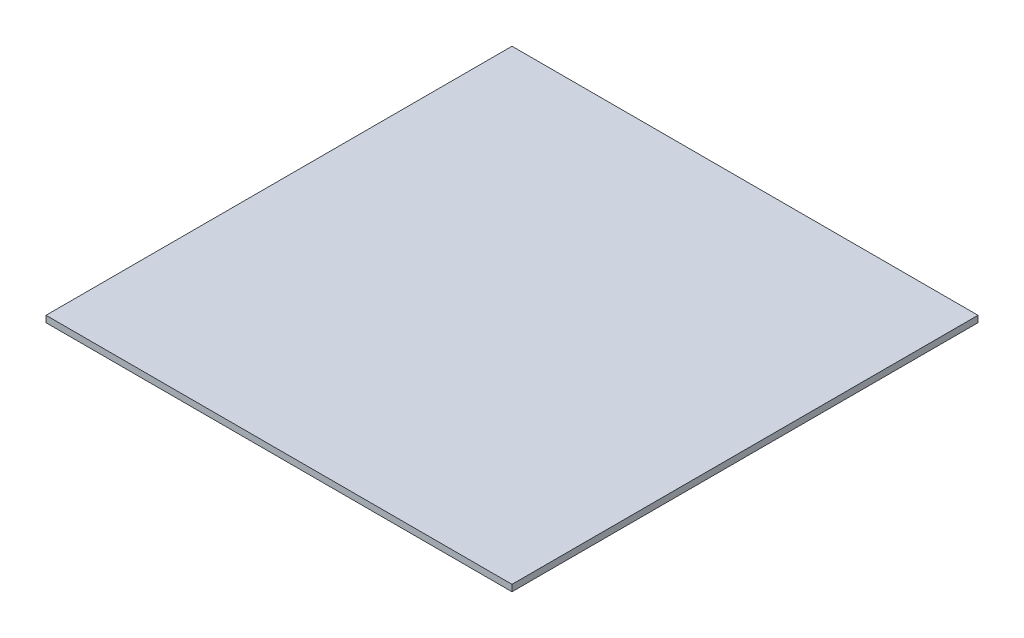
SolidWorks part; units mm, degrees
ref_plane "Front" through (0, 0, 0) normal (0, 0, 1) x (1, 0, 0)
ref_plane "Top" through (0, 0, 0) normal (0, 1, 0) x (1, 0, 0)
ref_plane "Right" through (0, 0, 0) normal (1, 0, 0) x (0, 0, -1)
sketch "Sketch1" plane through (0, 0, 0) normal (0, 1, 0) x (1, 0, 0)
  line L1 (-914.4, -914.4) -> (914.4, -914.4)
  line L2 (-914.4, -914.4) -> (-914.4, 914.4)
  line L3 (-914.4, 914.4) -> (914.4, 914.4)
  line L4 (914.4, -914.4) -> (914.4, 914.4)
  line L5 (-914.4, -914.4) -> (914.4, 914.4) construction
  line L6 (-914.4, 914.4) -> (914.4, -914.4) construction
  point P0 (0, 0)
  dimension "D1" = 1828.8
extrude "Extrude1" add sketch "Sketch1" against normal blind 25.4
